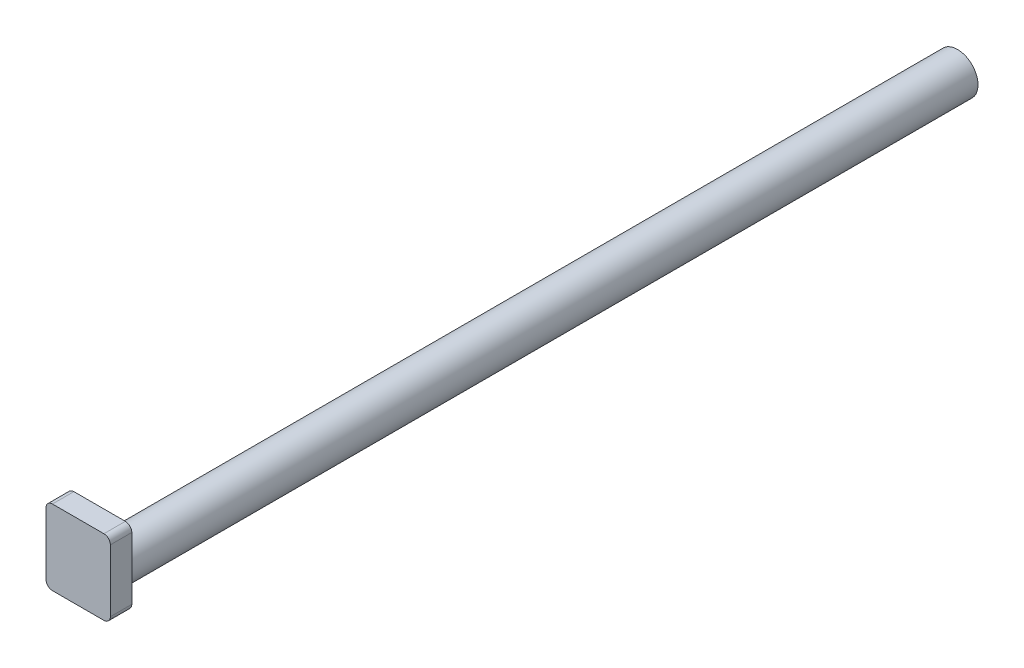
SolidWorks part; units mm, degrees
ref_plane "Front Plane" through (0, 0, 0) normal (0, 0, 1) x (1, 0, 0)
ref_plane "Top Plane" through (0, 0, 0) normal (0, 1, 0) x (1, 0, 0)
ref_plane "Right Plane" through (0, 0, 0) normal (1, 0, 0) x (0, 0, -1)
sketch "Sketch1" plane through (0, 0, 0) normal (0, 0, 1) x (1, 0, 0)
  circle A0 centre (0, 0) radius 9.525
  dimension "D1" = 19.05
extrude "Boss-Extrude1" add sketch "Sketch1" along normal blind 400
sketch "Sketch2" plane through (0, 0, 400) normal (0, 0, 1) x (1, 0, 0)
  line L0 (0, 0) -> (0, 25) construction
  line L1 (15, -10) -> (-15, -10)
  line L2 (15, -10) -> (15, 25)
  line L3 (15, 25) -> (-15, 25)
  line L4 (-15, -10) -> (-15, 25)
  point P0 (0, 0)
  dimension "D1" = 30
  dimension "D2" = 10
  dimension "D3" = 35
extrude "Boss-Extrude2" add sketch "Sketch2" along normal blind 10
fillet "Fillet1" radius 3 4 edges at (15, -10, 405) (-15, -10, 405) (-15, 25, 405) (15, 25, 405)
